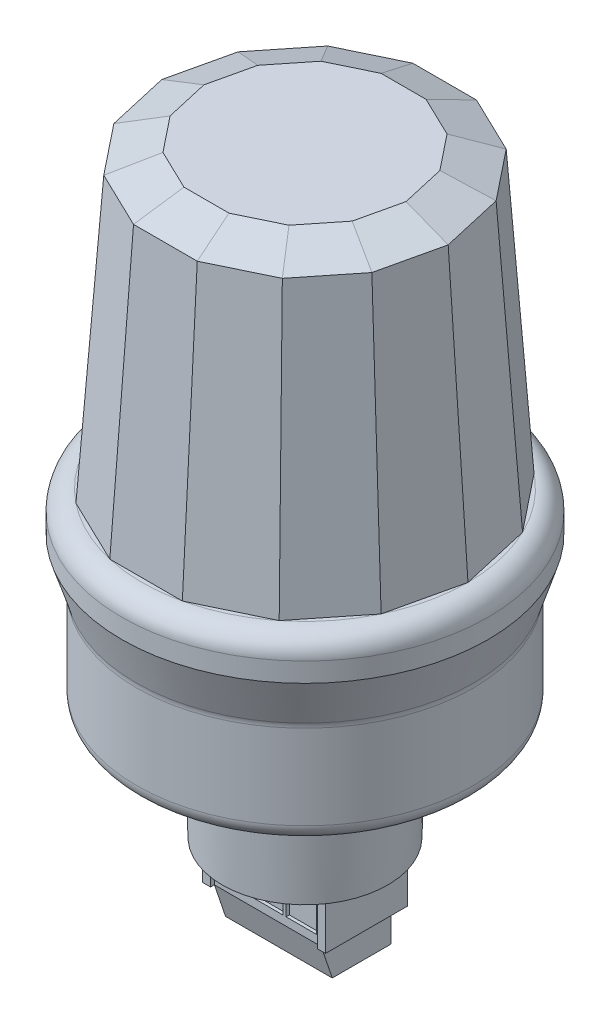
SolidWorks part; units mm, degrees
material "ABS"
ref_plane "Front" through (0, 0, 0) normal (0, 0, 1) x (1, 0, 0)
ref_plane "Top" through (0, 0, 0) normal (0, 1, 0) x (1, 0, 0)
ref_plane "Right" through (0, 0, 0) normal (1, 0, 0) x (0, 0, -1)
sketch "Sketch1" plane through (0, 0, 0) normal (0, 0, 1) x (1, 0, 0)
  line L0 (-13.335, 0) -> (-26.035, 0)
  line L1 (-26.035, 0) -> (-26.035, 16.002)
  line L2 (-26.035, 16.002) -> (-28.321, 23.241)
  line L3 (-28.321, 23.241) -> (0, 23.241)
  line L4 (0, 23.241) -> (0, -17.4)
  line L5 (0, -17.4) -> (-12.7932, -17.4)
  line L6 (-13.335, 0) -> (-12.7932, -17.4)
  line L7 (0, 0) -> (0, -86.7886) construction
  line L8 (-13.335, 0) -> (-13.335, -51.0989) construction
  dimension "D1" = 26.67
  dimension "D2" = 1.783
  dimension "D3" = 17.4
  dimension "D4" = 52.07
  dimension "D5" = 56.642
  dimension "D6" = 16.002
  dimension "D7" = 23.241
revolve "Revolve1" add sketch "Sketch1" angle 360 about L7
sketch "Sketch2" plane through (0, 23.241, 0) normal (0, 1, 0) x (1, 0, 0)
  line L0 (0, 0) -> (-19.067, 0) construction
  line L1 (-2.286, 5.08) -> (2.286, 5.08)
  line L2 (-2.286, 5.08) -> (-2.286, 4.318)
  line L3 (-2.286, 4.318) -> (2.286, 4.318)
  line L4 (2.286, 5.08) -> (2.286, 4.318)
  line L5 (0, 0) -> (0, 5.08) construction
  line L6 (3.2564, 4.5197) -> (5.5424, 0.5603)
  line L7 (3.2564, 4.5197) -> (2.5965, 4.1387)
  line L8 (2.5965, 4.1387) -> (4.8825, 0.1793)
  line L9 (5.5424, 0.5603) -> (4.8825, 0.1793)
  line L10 (5.5424, -0.5603) -> (3.2564, -4.5197)
  line L11 (5.5424, -0.5603) -> (4.8825, -0.1793)
  line L12 (4.8825, -0.1793) -> (2.5965, -4.1387)
  line L13 (3.2564, -4.5197) -> (2.5965, -4.1387)
  line L14 (2.286, -5.08) -> (-2.286, -5.08)
  line L15 (2.286, -5.08) -> (2.286, -4.318)
  line L16 (2.286, -4.318) -> (-2.286, -4.318)
  line L17 (-2.286, -5.08) -> (-2.286, -4.318)
  line L18 (-3.2564, -4.5197) -> (-5.5424, -0.5603)
  line L19 (-3.2564, -4.5197) -> (-2.5965, -4.1387)
  line L20 (-2.5965, -4.1387) -> (-4.8825, -0.1793)
  line L21 (-5.5424, -0.5603) -> (-4.8825, -0.1793)
  line L22 (-5.5424, 0.5603) -> (-3.2564, 4.5197)
  line L23 (-5.5424, 0.5603) -> (-4.8825, 0.1793)
  line L24 (-4.8825, 0.1793) -> (-2.5965, 4.1387)
  line L25 (-3.2564, 4.5197) -> (-2.5965, 4.1387)
  dimension "D1" = 4.572
  dimension "D2" = 10.16
  dimension "D3" = 0.762
  dimension "D4" = 6
extrude "Boss-Extrude1" add sketch "Sketch2" along normal blind 48.006
ref_plane "Plane1" through (0, 66.167, 0) normal (0, 1, 0) x (-1, 0, 0)
sketch "Sketch3" plane through (0, 66.167, 0) normal (0, 1, 0) x (-1, 0, 0)
  circle A0 centre (0, 0) radius 5.5707
extrude "Boss-Extrude2" add sketch "Sketch3" against normal blind 0.762
pattern_linear "LPattern1" count 2 spacing 19.05 along (0, -1, 0) of "Boss-Extrude2"
sketch "Sketch5" plane through (0, 0, 0) normal (1, 0, 0) x (0, 0, -1)
  line L0 (-5.08, 70.485) -> (-9.501, 69.8417)
  line L1 (-5.08, 71.247) -> (-5.08, 66.167) construction
  line L2 (-5.08, 71.247) -> (-4.318, 71.247) construction
  line L3 (-5.08, 68.199) -> (-5.08, 70.485)
  line L4 (-5.08, 68.199) -> (-10.922, 68.199) construction
  line L5 (-5.08, 68.199) -> (-10.922, 68.199)
  arc A0 (-9.501, 69.8417) -> (-10.922, 68.199) centre (-9.262, 68.199) ccw
  dimension "D1" = 4.572
  dimension "D2" = 5.842
  dimension "D3" = 0.762
revolve "Revolve2" add sketch "Sketch5" angle 360 about L4
pattern_linear "LPattern2" count 6 spacing 4.826 along (0, -1, 0) of "Revolve2"
pattern_circular "CirPattern1" count 6 over 360 about axis through (0, 0, 0) along (0, 1, 0) of "Revolve2", "LPattern2"
sketch "Sketch6" plane through (0, 0, 0) normal (0, 0, 1) x (1, 0, 0)
  line L0 (0, 29.337) -> (-25.2082, 29.337)
  line L1 (-28.321, 26.2242) -> (-28.321, 23.241)
  line L2 (0, 23.241) -> (0, 33.2954) construction
  line L3 (-2.286, 23.241) -> (2.286, 23.241) construction
  line L4 (28.321, 23.241) -> (-28.321, 23.241) construction
  line L5 (-28.321, 23.241) -> (0, 23.241)
  line L6 (0, 23.241) -> (0, 29.337)
  arc A0 (-25.2082, 29.337) -> (-28.321, 26.2242) centre (-25.2082, 26.2242) ccw
  dimension "D1" = 6.096
revolve "Revolve4" add sketch "Sketch6" angle 360 about L2
ref_plane "Plane2" through (0, 73.025, 0) normal (0, -1, 0) x (1, 0, 0)
sketch "Sketch7" plane through (0, 73.025, 0) normal (0, -1, 0) x (1, 0, 0)
  line L1 (4.9278, -21.59) -> (13.8073, -17.3138)
  line L2 (13.8073, -17.3138) -> (19.9522, -9.6085)
  line L3 (19.9522, -9.6085) -> (22.1452, 0)
  line L4 (22.1452, 0) -> (19.9522, 9.6085)
  line L5 (19.9522, 9.6085) -> (13.8073, 17.3138)
  line L6 (13.8073, 17.3138) -> (4.9278, 21.59)
  line L7 (4.9278, 21.59) -> (-4.9278, 21.59)
  line L8 (-4.9278, 21.59) -> (-13.8073, 17.3138)
  line L9 (-13.8073, 17.3138) -> (-19.9522, 9.6085)
  line L10 (-19.9522, 9.6085) -> (-22.1452, 0)
  line L11 (-22.1452, 0) -> (-19.9522, -9.6085)
  line L12 (-19.9522, -9.6085) -> (-13.8073, -17.3138)
  line L13 (-13.8073, -17.3138) -> (-4.9278, -21.59)
  line L14 (-4.9278, -21.59) -> (4.9278, -21.59)
  circle A0 centre (0, 0) radius 21.59 construction
  dimension "D1" = 43.18
sketch "Sketch8" plane through (0, 29.337, 0) normal (0, 1, 0) x (1, 0, 0)
  line L1 (5.6094, 24.5762) -> (-5.6094, 24.5762)
  line L2 (-5.6094, 24.5762) -> (-15.7171, 19.7086)
  line L3 (-15.7171, 19.7086) -> (-22.7118, 10.9374)
  line L4 (-22.7118, 10.9374) -> (-25.2082, 0)
  line L5 (-25.2082, 0) -> (-22.7118, -10.9374)
  line L6 (-22.7118, -10.9374) -> (-15.7171, -19.7086)
  line L7 (-15.7171, -19.7086) -> (-5.6094, -24.5762)
  line L8 (-5.6094, -24.5762) -> (5.6094, -24.5762)
  line L9 (5.6094, -24.5762) -> (15.7171, -19.7086)
  line L10 (15.7171, -19.7086) -> (22.7118, -10.9374)
  line L11 (22.7118, -10.9374) -> (25.2082, 0)
  line L12 (25.2082, 0) -> (22.7118, 10.9374)
  line L13 (22.7118, 10.9374) -> (15.7171, 19.7086)
  line L14 (15.7171, 19.7086) -> (5.6094, 24.5762)
  circle A0 centre (0, 0) radius 24.5762 construction
  circle A1 centre (0, 0) radius 25.2082 construction
ref_plane "Plane3" through (0, 75.565, 0) normal (0, -1, 0) x (1, 0, 0)
surface "Surface-Loft1"
sketch "Sketch14" plane through (0, 29.337, 0) normal (0, 1, 0) x (1, 0, 0)
  line L28 (5.4354, 23.8142) -> (-5.4354, 23.8142)
  line L29 (-5.4354, 23.8142) -> (-15.2297, 19.0975)
  line L30 (-15.2297, 19.0975) -> (-22.0076, 10.5983)
  line L31 (-22.0076, 10.5983) -> (-24.4266, 0)
  line L32 (-24.4266, 0) -> (-22.0076, -10.5983)
  line L33 (-22.0076, -10.5983) -> (-15.2297, -19.0975)
  line L34 (-15.2297, -19.0975) -> (-5.4354, -23.8142)
  line L35 (-5.4354, -23.8142) -> (5.4354, -23.8142)
  line L36 (5.4354, -23.8142) -> (15.2297, -19.0975)
  line L37 (15.2297, -19.0975) -> (22.0076, -10.5983)
  line L38 (22.0076, -10.5983) -> (24.4266, 0)
  line L39 (24.4266, 0) -> (22.0076, 10.5983)
  line L40 (22.0076, 10.5983) -> (15.2297, 19.0975)
  line L41 (15.2297, 19.0975) -> (5.4354, 23.8142)
  line L42 (5.4354, 23.8142) -> (-5.4354, 23.8142)
  line L43 (-5.4354, 23.8142) -> (-15.2297, 19.0975)
  line L44 (-15.2297, 19.0975) -> (-22.0076, 10.5983)
  line L45 (-22.0076, 10.5983) -> (-24.4266, 0)
  line L46 (-24.4266, 0) -> (-22.0076, -10.5983)
  line L47 (-22.0076, -10.5983) -> (-15.2297, -19.0975)
  line L48 (-15.2297, -19.0975) -> (-5.4354, -23.8142)
  line L49 (-5.4354, -23.8142) -> (5.4354, -23.8142)
  line L50 (5.4354, -23.8142) -> (15.2297, -19.0975)
  line L51 (15.2297, -19.0975) -> (22.0076, -10.5983)
  line L52 (22.0076, -10.5983) -> (24.4266, 0)
  line L53 (24.4266, 0) -> (22.0076, 10.5983)
  line L54 (22.0076, 10.5983) -> (15.2297, 19.0975)
  line L55 (15.2297, 19.0975) -> (5.4354, 23.8142)
  dimension "D1" = 0.762
sketch "Sketch15" plane through (0, 73.025, 0) normal (0, -1, 0) x (1, 0, 0)
  line L28 (4.7539, -20.828) -> (13.32, -16.7028)
  line L29 (13.32, -16.7028) -> (19.248, -9.2693)
  line L30 (19.248, -9.2693) -> (21.3636, 0)
  line L31 (21.3636, 0) -> (19.248, 9.2693)
  line L32 (19.248, 9.2693) -> (13.32, 16.7028)
  line L33 (13.32, 16.7028) -> (4.7539, 20.828)
  line L34 (4.7539, 20.828) -> (-4.7539, 20.828)
  line L35 (-4.7539, 20.828) -> (-13.32, 16.7028)
  line L36 (-13.32, 16.7028) -> (-19.248, 9.2693)
  line L37 (-19.248, 9.2693) -> (-21.3636, 0)
  line L38 (-21.3636, 0) -> (-19.248, -9.2693)
  line L39 (-19.248, -9.2693) -> (-13.32, -16.7028)
  line L40 (-13.32, -16.7028) -> (-4.7539, -20.828)
  line L41 (-4.7539, -20.828) -> (4.7539, -20.828)
  line L42 (4.7539, -20.828) -> (13.32, -16.7028)
  line L43 (13.32, -16.7028) -> (19.248, -9.2693)
  line L44 (19.248, -9.2693) -> (21.3636, 0)
  line L45 (21.3636, 0) -> (19.248, 9.2693)
  line L46 (19.248, 9.2693) -> (13.32, 16.7028)
  line L47 (13.32, 16.7028) -> (4.7539, 20.828)
  line L48 (4.7539, 20.828) -> (-4.7539, 20.828)
  line L49 (-4.7539, 20.828) -> (-13.32, 16.7028)
  line L50 (-13.32, 16.7028) -> (-19.248, 9.2693)
  line L51 (-19.248, 9.2693) -> (-21.3636, 0)
  line L52 (-21.3636, 0) -> (-19.248, -9.2693)
  line L53 (-19.248, -9.2693) -> (-13.32, -16.7028)
  line L54 (-13.32, -16.7028) -> (-4.7539, -20.828)
  line L55 (-4.7539, -20.828) -> (4.7539, -20.828)
  dimension "D1" = 0.762
surface "Surface-Loft2"
sketch "Sketch16" plane through (0, 73.025, 0) normal (0, -1, 0) x (1, 0, 0)
  line L14 (4.9278, -21.59) -> (13.8073, -17.3138)
  line L15 (13.8073, -17.3138) -> (19.9522, -9.6085)
  line L16 (19.9522, -9.6085) -> (22.1452, 0)
  line L17 (22.1452, 0) -> (19.9522, 9.6085)
  line L18 (19.9522, 9.6085) -> (13.8073, 17.3138)
  line L19 (13.8073, 17.3138) -> (4.9278, 21.59)
  line L20 (4.9278, 21.59) -> (-4.9278, 21.59)
  line L21 (-4.9278, 21.59) -> (-13.8073, 17.3138)
  line L22 (-13.8073, 17.3138) -> (-19.9522, 9.6085)
  line L23 (-19.9522, 9.6085) -> (-22.1452, 0)
  line L24 (-22.1452, 0) -> (-19.9522, -9.6085)
  line L25 (-19.9522, -9.6085) -> (-13.8073, -17.3138)
  line L26 (-13.8073, -17.3138) -> (-4.9278, -21.59)
  line L27 (-4.9278, -21.59) -> (4.9278, -21.59)
  line L28 (4.9278, -21.59) -> (13.8073, -17.3138)
  line L29 (13.8073, -17.3138) -> (19.9522, -9.6085)
  line L30 (19.9522, -9.6085) -> (22.1452, 0)
  line L31 (22.1452, 0) -> (19.9522, 9.6085)
  line L32 (19.9522, 9.6085) -> (13.8073, 17.3138)
  line L33 (13.8073, 17.3138) -> (4.9278, 21.59)
  line L34 (4.9278, 21.59) -> (-4.9278, 21.59)
  line L35 (-4.9278, 21.59) -> (-13.8073, 17.3138)
  line L36 (-13.8073, 17.3138) -> (-19.9522, 9.6085)
  line L37 (-19.9522, 9.6085) -> (-22.1452, 0)
  line L38 (-22.1452, 0) -> (-19.9522, -9.6085)
  line L39 (-19.9522, -9.6085) -> (-13.8073, -17.3138)
  line L40 (-13.8073, -17.3138) -> (-4.9278, -21.59)
  line L41 (-4.9278, -21.59) -> (4.9278, -21.59)
  dimension "D1" = 0
sketch "Sketch17" plane through (0, 75.565, 0) normal (0, -1, 0) x (1, 0, 0)
  line L1 (3.4784, -15.24) -> (9.7463, -12.2215)
  line L2 (9.7463, -12.2215) -> (14.0839, -6.7824)
  line L3 (14.0839, -6.7824) -> (15.6319, 0)
  line L4 (15.6319, 0) -> (14.0839, 6.7824)
  line L5 (14.0839, 6.7824) -> (9.7463, 12.2215)
  line L6 (9.7463, 12.2215) -> (3.4784, 15.24)
  line L7 (3.4784, 15.24) -> (-3.4784, 15.24)
  line L8 (-3.4784, 15.24) -> (-9.7463, 12.2215)
  line L9 (-9.7463, 12.2215) -> (-14.0839, 6.7824)
  line L10 (-14.0839, 6.7824) -> (-15.6319, 0)
  line L11 (-15.6319, 0) -> (-14.0839, -6.7824)
  line L12 (-14.0839, -6.7824) -> (-9.7463, -12.2215)
  line L13 (-9.7463, -12.2215) -> (-3.4784, -15.24)
  line L14 (-3.4784, -15.24) -> (3.4784, -15.24)
  circle A0 centre (0, 0) radius 15.24 construction
  dimension "D1" = 30.48
loft "Loft5" add profiles "Sketch16", "Sketch17"
sketch "Sketch18" plane through (0, -17.4, 0) normal (0, -1, 0) x (1, 0, 0)
  line L0 (-8.255, 5.08) -> (8.255, 5.08)
  line L1 (-9.525, -6.35) -> (9.525, -6.35)
  line L2 (-9.525, -6.35) -> (-9.525, 6.35)
  line L3 (-9.525, 6.35) -> (9.525, 6.35)
  line L4 (9.525, -6.35) -> (9.525, 6.35)
  line L5 (-9.525, -6.35) -> (9.525, 6.35) construction
  line L6 (-9.525, 6.35) -> (9.525, -6.35) construction
  line L7 (8.255, -5.08) -> (8.255, 5.08)
  line L8 (-8.255, -5.08) -> (8.255, -5.08)
  line L9 (-8.255, -5.08) -> (-8.255, 5.08)
  point P0 (0, 0)
  dimension "D1" = 1.27
extrude "Boss-Extrude3" add sketch "Sketch18" along normal blind 7.62
sketch "Sketch19" plane through (0, 0, 6.35) normal (0, 0, 1) x (1, 0, 0)
  line L0 (-8.255, -25.02) -> (-8.255, -17.4)
  line L1 (9.525, -17.4) -> (-9.525, -17.4) construction
  line L2 (-8.255, -17.4) -> (8.255, -17.4)
  line L3 (8.255, -17.4) -> (8.255, -25.02)
  line L4 (9.525, -25.02) -> (-9.525, -25.02) construction
  line L5 (0, 0) -> (0, -28.8291) construction
  line L6 (-13.335, 0) -> (13.335, 0) construction
  line L7 (-8.255, -25.02) -> (8.255, -25.02)
extrude "Cut-Extrude1" cut sketch "Sketch19" against normal up to next (1.27 mm away)
sketch "Sketch20" plane through (0, 0, -6.35) normal (0, 0, -1) x (-1, 0, 0)
  line L0 (9.525, -17.4) -> (-9.525, -17.4) construction
  line L1 (9.525, -25.02) -> (-9.525, -25.02) construction
  circle A0 centre (0, -25.02) radius 7.62
extrude "Cut-Extrude2" cut sketch "Sketch20" against normal up to next (1.27 mm away)
sketch "Sketch21" plane through (0, 0, 0) normal (1, 0, 0) x (0, 0, -1)
  line L0 (5.08, -17.4) -> (5.08, -30.1)
  line L1 (5.08, -25.02) -> (5.08, -17.4) construction
  line L2 (5.08, -30.1) -> (-4.0364, -30.1)
  line L3 (-4.0364, -30.1) -> (-5.7537, -25.02)
  line L5 (-5.7537, -25.02) -> (-5.7537, -17.4)
  line L6 (-12.7932, -17.4) -> (12.7932, -17.4) construction
  line L7 (6.35, -25.02) -> (-6.35, -25.02) construction
  line L8 (-5.7537, -17.4) -> (5.08, -17.4)
  dimension "D1" = 12.7
extrude "Boss-Extrude4" add sketch "Sketch21" along normal mid plane 16.51
sketch "Sketch22" plane through (0, 0, 5.7537) normal (0, 0, 1) x (1, 0, 0)
  line L0 (0, -17.4) -> (0, -27.858) construction
  line L1 (-7.5498, -17.8521) -> (-2.835, -17.8521)
  line L2 (-7.5498, -17.8521) -> (-7.5498, -23.7618)
  line L3 (-7.5498, -23.7618) -> (-2.835, -23.7618)
  line L4 (-2.835, -17.8521) -> (-2.835, -23.7618)
  line L5 (-7.5498, -17.8521) -> (-2.835, -23.7618) construction
  line L6 (-7.5498, -23.7618) -> (-2.835, -17.8521) construction
  line L7 (8.255, -17.4) -> (-8.255, -17.4) construction
  line L8 (7.5498, -23.7618) -> (2.835, -17.8521) construction
  line L9 (7.5498, -17.8521) -> (2.835, -23.7618) construction
  line L10 (2.835, -17.8521) -> (2.835, -23.7618)
  line L11 (7.5498, -23.7618) -> (2.835, -23.7618)
  line L12 (7.5498, -17.8521) -> (7.5498, -23.7618)
  line L13 (7.5498, -17.8521) -> (2.835, -17.8521)
  line L15 (-2.3574, -23.7618) -> (2.3574, -23.7618)
  line L16 (-2.3574, -23.7618) -> (-2.3574, -17.8521)
  line L17 (-2.3574, -17.8521) -> (2.3574, -17.8521)
  line L18 (2.3574, -23.7618) -> (2.3574, -17.8521)
  line L19 (-2.3574, -23.7618) -> (2.3574, -17.8521) construction
  line L20 (-2.3574, -17.8521) -> (2.3574, -23.7618) construction
  point P0 (-5.1924, -20.8069)
  point P14 (5.1924, -20.8069)
  point P15 (0, -20.8069)
extrude "Cut-Extrude3" cut sketch "Sketch22" against normal blind 0.508
sketch "Sketch23" plane through (0, -30.1, 0) normal (0, -1, 0) x (1, 0, 0)
  line L0 (-5.1924, 0) -> (5.1924, 0) construction
  line L1 (-5.1924, 5.2457) -> (-5.1924, 0) construction
  line L2 (-2.835, 5.2457) -> (-7.5498, 5.2457) construction
  circle A0 centre (-5.1924, 0) radius 1.997
  circle A1 centre (0, 0) radius 1.997
  circle A2 centre (5.1924, 0) radius 1.997
extrude "Cut-Extrude4" cut sketch "Sketch23" against normal blind 1.27
fillet "Fillet1" radius 2.54 2 edges at (0, 16.002, 26.035) (0, 0, 26.035)
